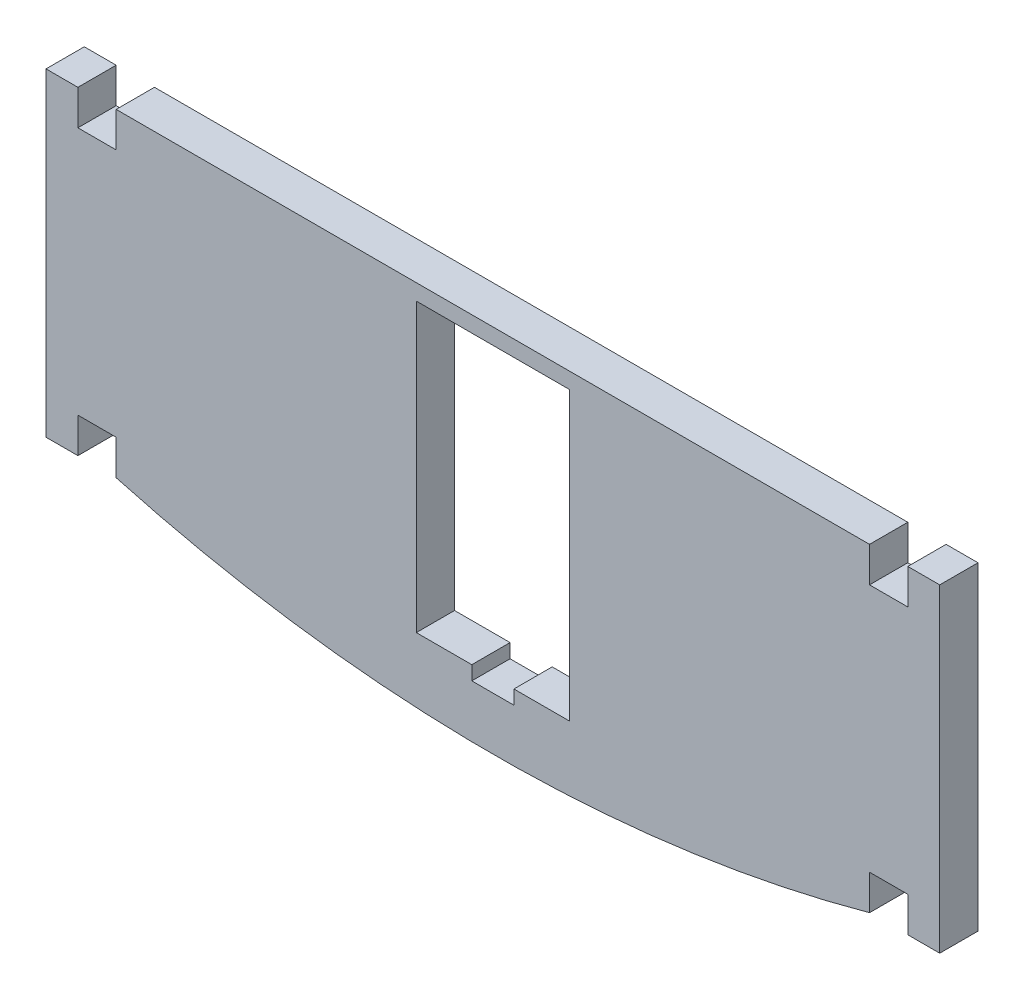
SolidWorks part; units mm, degrees
ref_plane "Ebene vorne" through (0, 0, 0) normal (0, 0, 1) x (1, 0, 0)
ref_plane "Ebene oben" through (0, 0, 0) normal (0, 1, 0) x (1, 0, 0)
ref_plane "Ebene rechts" through (0, 0, 0) normal (1, 0, 0) x (0, 0, -1)
sketch "Skizze1" plane through (0, 0, 0) normal (0, 0, 1) x (1, 0, 0)
  line L20 (-6, -11.25) -> (0, -11.25)
  line L21 (-6, 11.25) -> (0, 11.25)
  line L22 (-35.018, 12.5) -> (-35.018, -12.5)
  line L23 (-6, 11.25) -> (-6, -11.25)
  line L24 (-35.018, 0) -> (24.9058, 0) construction
  line L25 (0, 16.5) -> (0, -16.5) construction
  line L26 (0, 16.5) -> (0, 11.25)
  line L27 (0, -11.25) -> (0, -16.5)
  line L32 (-29.518, 12.5) -> (-29.518, 9.75)
  line L33 (-29.518, 9.75) -> (-32.518, 9.75)
  line L34 (-32.518, 9.75) -> (-32.518, 12.5)
  line L35 (-32.518, 12.5) -> (-35.018, 12.5)
  line L36 (-35.018, -12.5) -> (-32.518, -12.5)
  line L37 (-32.518, -12.5) -> (-32.518, -9.75)
  line L38 (-32.518, -9.75) -> (-29.518, -9.75)
  line L39 (-29.518, -9.75) -> (-29.518, -12.5)
  arc A23 (-29.518, -12.5) -> (0, -16.5) centre (0, 94.4144) ccw
  arc A29 (0, 16.5) -> (-29.518, 12.5) centre (0, -94.4144) ccw
  dimension "D1" = 19.5
  dimension "D2" = 59.0361
  dimension "D3" = 3
  dimension "D4" = 25
  dimension "D5" = 2.5
  dimension "D6" = 33
  dimension "D9" = 12
  dimension "D10" = 22.5
extrude "Aufsatz-Linear austragen1" add sketch "Skizze1" against normal blind 3
mirror "Spiegeln1" about plane through (0, 0, 0) normal (1, 0, 0) of "Aufsatz-Linear austragen1"
sketch "Skizze2" plane through (0, 0, 0) normal (0, 0, 1) x (1, 0, 0)
  line L0 (29.518, 12.5) -> (-29.518, 12.5)
  line L1 (29.518, 12.5) -> (29.518, 9.75) construction
  arc A0 (29.518, 12.5) -> (-29.518, 12.5) centre (0, -94.4144) ccw construction
extrude "Schnitt-Linear austragen2" cut sketch "Skizze2" against normal through all and the other way through all flip side to cut
hole_wizard "Ø1.0 (1) Durchmesser Bohrung1" positions "Skizze3" profile "Skizze4" hole size "Ø1.0" standard "DIN"
sketch "Skizze3" plane through (0, 0, 0) normal (0, 0, 1) x (1, 0, 0)
  point P0 (0, 14)
  point P3 (0, -14)
sketch "Skizze4" plane through (0, 14, 0) normal (1, 0, 0) x (0, -1, 0)
  line L0 (0, 0) -> (0, 3)
  line L1 (0, 3) -> (0.5, 3)
  line L2 (0.5, 3) -> (0.5, 0)
  line L5 (0.5, 0) -> (0, 0)
  line L11 (0, -6.35) -> (0, 107.95) construction
  dimension "Bohrerdurchmesser" = 1
  dimension "Bohrungstiefe" = 3
sketch "Skizze5" plane through (0, 0, 0) normal (0, 0, 1) x (1, 0, 0)
  line L0 (6, -11.25) -> (-6, -11.25) construction
  line L1 (-1.65, -11.25) -> (1.65, -11.25)
  line L2 (-1.65, -11.25) -> (-1.65, -12.35)
  line L3 (-1.65, -12.35) -> (1.65, -12.35)
  line L4 (1.65, -11.25) -> (1.65, -12.35)
  point P6 (0, -11.25)
  dimension "D1" = 1.1
  dimension "D2" = 3.3
extrude "Schnitt-Linear austragen3" cut sketch "Skizze5" against normal blind 10
